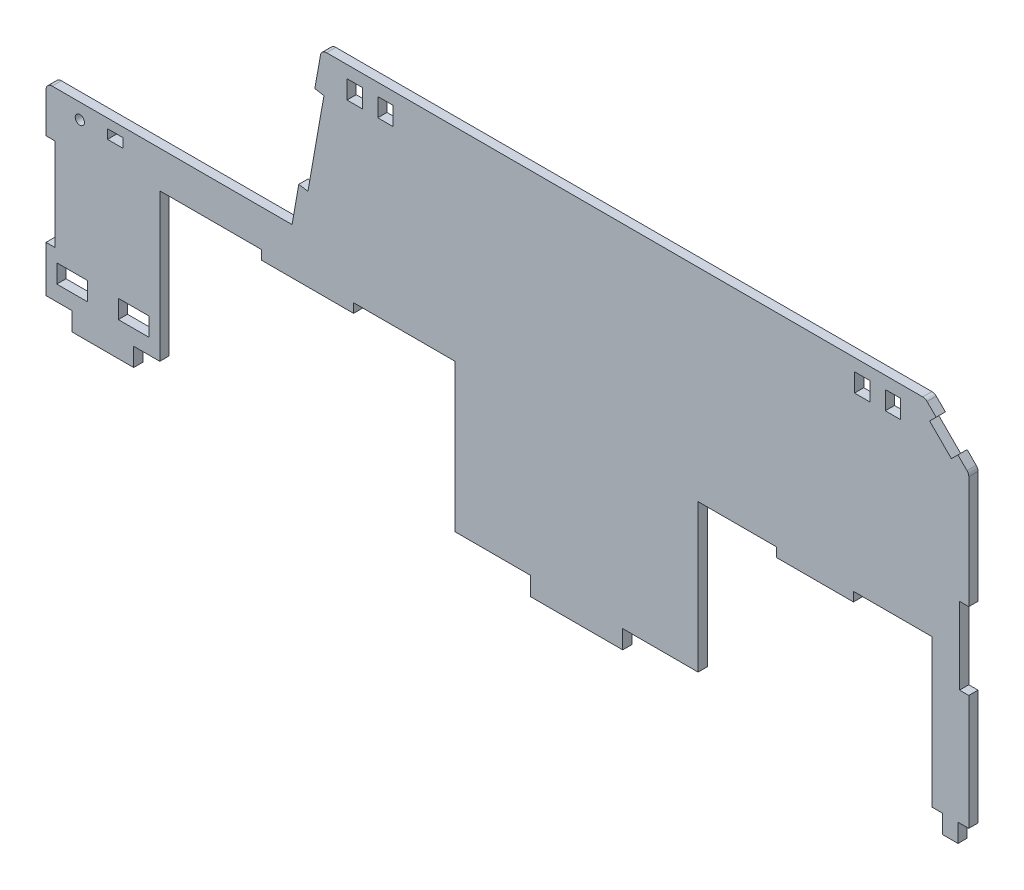
SolidWorks part; units mm, degrees
ref_plane "Front Plane" through (0, 0, 0) normal (0, 0, 1) x (1, 0, 0)
ref_plane "Top Plane" through (0, 0, 0) normal (0, 1, 0) x (1, 0, 0)
ref_plane "Right Plane" through (0, 0, 0) normal (1, 0, 0) x (0, 0, -1)
sketch "Sketch1" plane through (0, 0, 0) normal (0, 0, 1) x (1, 0, 0)
  line L0 (0, 0) -> (8.5, 0)
  line L1 (8.5, 0) -> (8.5, -6)
  line L2 (8.5, -6) -> (28.5, -6)
  line L3 (28.5, -6) -> (28.5, 0)
  line L4 (28.5, 0) -> (37, 0)
  line L5 (37, 0) -> (37, 48)
  line L6 (37, 48) -> (70, 48)
  line L7 (70, 48) -> (70, 45)
  line L8 (70, 45) -> (100, 45)
  line L9 (100, 45) -> (100, 48)
  line L10 (100, 48) -> (133, 48)
  line L11 (133, 48) -> (133, 0)
  line L12 (133, 0) -> (157.5, 0)
  line L13 (157.5, 0) -> (157.5, -6)
  line L14 (157.5, -6) -> (187.5, -6)
  line L15 (187.5, -6) -> (187.5, 0)
  line L16 (187.5, 0) -> (212, 0)
  line L17 (212, 0) -> (212, 48)
  line L18 (212, 48) -> (237.5, 48)
  line L19 (237.5, 48) -> (237.5, 45)
  line L20 (237.5, 45) -> (262.5, 45)
  line L21 (262.5, 45) -> (262.5, 48)
  line L22 (262.5, 48) -> (288, 48)
  line L23 (288, 48) -> (288, 0)
  line L24 (288, 0) -> (291.5, 0)
  line L25 (291.5, 0) -> (291.5, -6)
  line L26 (291.5, -6) -> (296.5, -6)
  line L27 (296.5, -6) -> (296.5, 0)
  line L28 (296.5, 0) -> (300, 0)
  line L29 (300, 0) -> (300, 37.4289)
  line L30 (300, 37.4289) -> (297, 37.4289)
  line L31 (297, 37.4289) -> (297, 62.4289)
  line L32 (297, 62.4289) -> (300, 62.4289)
  line L33 (300, 62.4289) -> (300, 99.8579)
  line L34 (300, 99.8579) -> (296.4645, 103.3934)
  line L35 (296.4645, 103.3934) -> (294.3431, 101.2721)
  line L36 (294.3431, 101.2721) -> (287.2721, 108.3431)
  line L37 (287.2721, 108.3431) -> (289.3934, 110.4645)
  line L38 (289.3934, 110.4645) -> (285.8579, 114)
  line L39 (285.8579, 114) -> (89.5217, 114)
  line L40 (89.5217, 114) -> (80, 60)
  line L41 (80, 60) -> (0, 60)
  line L42 (0, 60) -> (0, 0)
  dimension "D1" = 76
  dimension "D2" = 96
  dimension "D3" = 79
  dimension "D4" = 6
  dimension "D5" = 3
  dimension "D6" = 120
  dimension "D7" = 25
  dimension "D8" = 3
  dimension "D9" = 3
  dimension "D10" = 10
  dimension "D11" = 5
  dimension "D12" = 48
  dimension "D13" = 25
  dimension "D14" = 30
  dimension "D15" = 30
  dimension "D16" = 5
  dimension "D17" = 20
  dimension "D18" = 300
  dimension "D19" = 12
  dimension "D20" = 60
  dimension "D21" = 80
  dimension "D22" = 135
  dimension "D23" = 100
extrude "Boss-Extrude1" add sketch "Sketch1" along normal blind 3
sketch "Sketch2" plane through (0, 0, 0) normal (0, 0, -1) x (-1, 0, 0)
  line L0 (-89.5217, 114) -> (-80, 60) construction
  line L1 (-87.4057, 102) -> (-90.3602, 101.4791)
  line L2 (-87.4057, 102) -> (-82.1963, 72.4558)
  line L3 (-82.1963, 72.4558) -> (-85.1507, 71.9348)
  line L4 (-90.3602, 101.4791) -> (-85.1507, 71.9348)
  line L5 (0, 60) -> (0, 0) construction
  line L6 (0, 45) -> (-3, 45)
  line L7 (0, 45) -> (0, 15)
  line L8 (0, 15) -> (-3, 15)
  line L9 (-3, 45) -> (-3, 15)
  line L11 (-80, 60) -> (0, 60) construction
  line L12 (-285.8579, 114) -> (-89.5217, 114) construction
  dimension "D1" = 3
  dimension "D2" = 30
  dimension "D3" = 12
  dimension "D4" = 30
  dimension "D5" = 15
extrude "Cut-Extrude1" cut sketch "Sketch2" against normal through all
sketch "Sketch3" plane through (0, 0, 0) normal (0, 0, -1) x (-1, 0, 0)
  line L0 (-37, 0) -> (-37, 48) construction
  line L1 (-33.5, 11) -> (-23.5, 11)
  line L2 (-33.5, 11) -> (-33.5, 5)
  line L3 (-33.5, 5) -> (-23.5, 5)
  line L4 (-23.5, 11) -> (-23.5, 5)
  line L5 (-13.5, 11) -> (-3.5, 11)
  line L6 (-13.5, 11) -> (-13.5, 5)
  line L7 (-13.5, 5) -> (-3.5, 5)
  line L8 (-3.5, 11) -> (-3.5, 5)
  line L9 (-28.5, 0) -> (-37, 0) construction
  dimension "D1" = 30
  dimension "D2" = 10
  dimension "D3" = 6
  dimension "D4" = 3.5
  dimension "D5" = 5
extrude "Cut-Extrude2" cut sketch "Sketch3" against normal through all
sketch "Sketch4" plane through (0, 0, 0) normal (0, 0, -1) x (-1, 0, 0)
  line L0 (-80, 60) -> (0, 60) construction
  line L1 (0, 60) -> (0, 45) construction
  line L3 (-25, 57) -> (-20, 57)
  line L4 (-25, 57) -> (-25, 54)
  line L5 (-25, 54) -> (-20, 54)
  line L6 (-20, 57) -> (-20, 54)
  circle A0 centre (-11, 55) radius 1.5
  dimension "D1" = 3
  dimension "D2" = 5
  dimension "D3" = 11
  dimension "D4" = 5
  dimension "D5" = 3
  dimension "D6" = 3
  dimension "D7" = 20
extrude "Cut-Extrude3" cut sketch "Sketch4" against normal through all
sketch "Sketch5" plane through (0, 0, 0) normal (0, 0, -1) x (-1, 0, 0)
  line L0 (-285.8579, 114) -> (-89.5217, 114) construction
  line L1 (-277.8579, 110) -> (-272.8579, 110)
  line L2 (-277.8579, 110) -> (-277.8579, 104)
  line L3 (-277.8579, 104) -> (-272.8579, 104)
  line L4 (-272.8579, 110) -> (-272.8579, 104)
  line L5 (-267.8579, 110) -> (-262.8579, 110)
  line L6 (-267.8579, 110) -> (-267.8579, 104)
  line L7 (-267.8579, 104) -> (-262.8579, 104)
  line L8 (-262.8579, 110) -> (-262.8579, 104)
  line L9 (-112.8579, 110) -> (-107.8579, 110)
  line L10 (-112.8579, 110) -> (-112.8579, 104)
  line L11 (-112.8579, 104) -> (-107.8579, 104)
  line L12 (-107.8579, 110) -> (-107.8579, 104)
  line L13 (-102.8579, 110) -> (-97.8579, 110)
  line L14 (-102.8579, 110) -> (-102.8579, 104)
  line L15 (-102.8579, 104) -> (-97.8579, 104)
  line L16 (-97.8579, 110) -> (-97.8579, 104)
  dimension "D1" = 5
  dimension "D2" = 5
  dimension "D3" = 6
  dimension "D4" = 4
  dimension "D5" = 8
  dimension "D6" = 150
  dimension "D7" = 5
extrude "Cut-Extrude4" cut sketch "Sketch5" against normal through all
fillet "Fillet1" radius 2 4 edges at (0, 60, 1.5) (89.5217, 114, 1.5) (285.8579, 114, 1.5) (300, 99.8579, 1.5)
